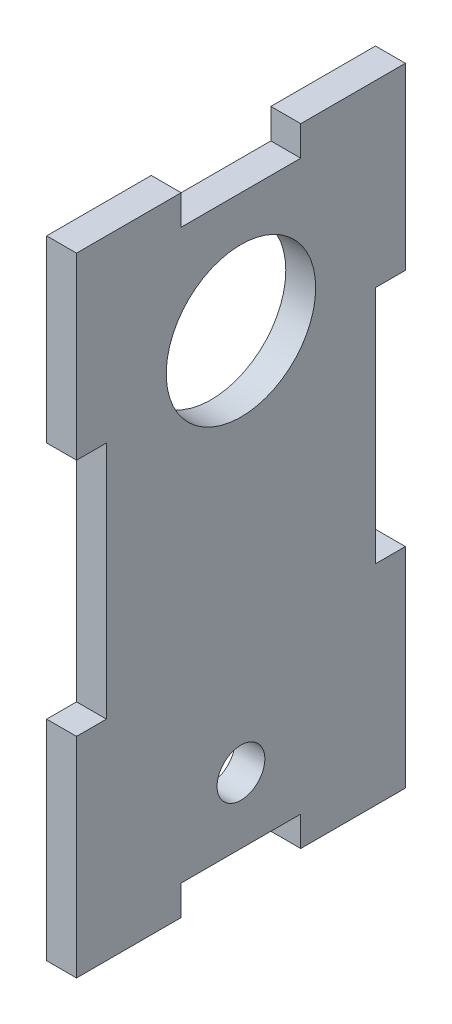
SolidWorks part; units mm, degrees
ref_plane "前视基准面" through (0, 0, 0) normal (0, 0, 1) x (1, 0, 0)
ref_plane "上视基准面" through (0, 0, 0) normal (0, 1, 0) x (1, 0, 0)
ref_plane "右视基准面" through (0, 0, 0) normal (1, 0, 0) x (0, 0, -1)
sketch "草图1" plane through (0, 0, 0) normal (1, 0, 0) x (0, 0, -1)
  line L0 (-38.9375, 64.0445) -> (-56.4375, 64.0445)
  line L1 (-1.4375, -40.9555) -> (-18.9375, -40.9555)
  line L2 (-1.4375, -40.9555) -> (-1.4375, -5.9555)
  line L3 (-1.4375, 64.0445) -> (-18.9375, 64.0445)
  line L4 (-56.4375, -40.9555) -> (-56.4375, -5.9555)
  line L5 (-56.4375, 34.0445) -> (-51.4375, 34.0445)
  line L6 (-1.4375, 34.0445) -> (-1.4375, 64.0445)
  line L7 (-56.4375, -5.9555) -> (-51.4375, -5.9555)
  line L8 (-51.4375, 34.0445) -> (-51.4375, -5.9555)
  line L9 (-56.4375, 34.0445) -> (-56.4375, 64.0445)
  line L10 (-38.9375, 64.0445) -> (-38.9375, 59.0445)
  line L11 (-38.9375, 59.0445) -> (-18.9375, 59.0445)
  line L12 (-18.9375, 64.0445) -> (-18.9375, 59.0445)
  line L13 (-1.4375, 34.0445) -> (-6.4375, 34.0445)
  line L14 (-38.9375, -40.9555) -> (-56.4375, -40.9555)
  line L15 (-1.4375, -5.9555) -> (-6.4375, -5.9555)
  line L16 (-6.4375, 34.0445) -> (-6.4375, -5.9555)
  line L17 (-28.9375, 76.2301) -> (-28.9375, -55.2095) construction
  line L18 (-38.9375, -40.9555) -> (-38.9375, -35.9555)
  line L19 (-38.9375, -35.9555) -> (-18.9375, -35.9555)
  line L20 (-18.9375, -40.9555) -> (-18.9375, -35.9555)
  circle A0 centre (-28.9375, -24.9555) radius 4
  circle A1 centre (-28.9375, 39.0445) radius 12.5
  point P26 (-28.9375, 39.0445)
  point P41 (-1.4375, -40.9555)
  point P56 (-35.6561, 42.9374)
  point P57 (-28.9375, 39.0445)
  dimension "D17" = 25
  dimension "D1" = 105
  dimension "D2" = 55
  dimension "D3" = 5
  dimension "D4" = 5
  dimension "D5" = 5
  dimension "D6" = 20
  dimension "D7" = 40
  dimension "D8" = 40
  dimension "D9" = 20
  dimension "D10" = 5
  dimension "D11" = 17.5
  dimension "D12" = 17.5
  dimension "D13" = 35
  dimension "D14" = 35
  dimension "D15" = 22.5
  dimension "D16" = 11
  dimension "D20" = 0
  dimension "D21" = 20
  dimension "D23" = 64
extrude "凸台-拉伸1" add sketch "草图1" along normal blind 5
